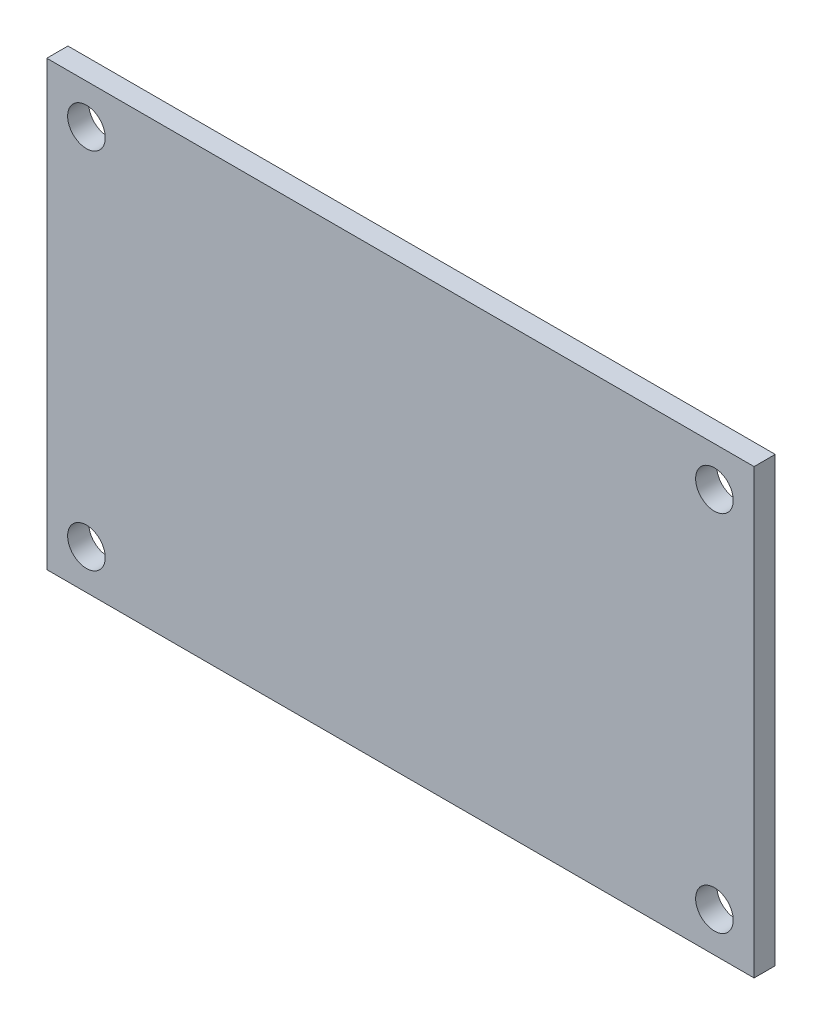
SolidWorks part; units mm, degrees
ref_plane "Front Plane" through (0, 0, 0) normal (0, 0, 1) x (1, 0, 0)
ref_plane "Top Plane" through (0, 0, 0) normal (0, 1, 0) x (1, 0, 0)
ref_plane "Right Plane" through (0, 0, 0) normal (1, 0, 0) x (0, 0, -1)
sketch "Sketch1" plane through (0, 0, 0) normal (0, 0, 1) x (1, 0, 0)
  line L1 (0, 0) -> (53.5, 0)
  line L2 (0, 0) -> (0, -33.5)
  line L3 (0, -33.5) -> (53.5, -33.5)
  line L4 (53.5, 0) -> (53.5, -33.5)
  dimension "D1" = 53.5
  dimension "D2" = 33.5
extrude "Boss-Extrude1" add sketch "Sketch1" along normal blind 1.6
sketch "Sketch2" plane through (0, 0, 1.6) normal (0, 0, 1) x (1, 0, 0)
  line L0 (26.75, 0) -> (26.75, -33.5) construction
  line L1 (53.5, 0) -> (0, 0) construction
  line L2 (0, -33.5) -> (53.5, -33.5) construction
  line L3 (0, -16.75) -> (53.5, -16.75) construction
  line L4 (0, 0) -> (0, -33.5) construction
  line L5 (53.5, -33.5) -> (53.5, 0) construction
  line L6 (3, -3) -> (50.5, -3) construction
  line L7 (50.5, -3) -> (50.5, -30.5) construction
  line L8 (50.5, -30.5) -> (3, -30.5) construction
  line L9 (3, -30.5) -> (3, -3) construction
  circle A0 centre (3, -3) radius 1.4224
  circle A1 centre (50.5, -3) radius 1.4224
  circle A2 centre (3, -30.5) radius 1.4224
  circle A3 centre (50.5, -30.5) radius 1.4224
  point P20 (3, -16.75)
  point P21 (26.75, -3)
  dimension "D3" = 2.8448
  dimension "D1" = 47.5
  dimension "D2" = 27.5
extrude "Cut-Extrude1" cut sketch "Sketch2" against normal through all
